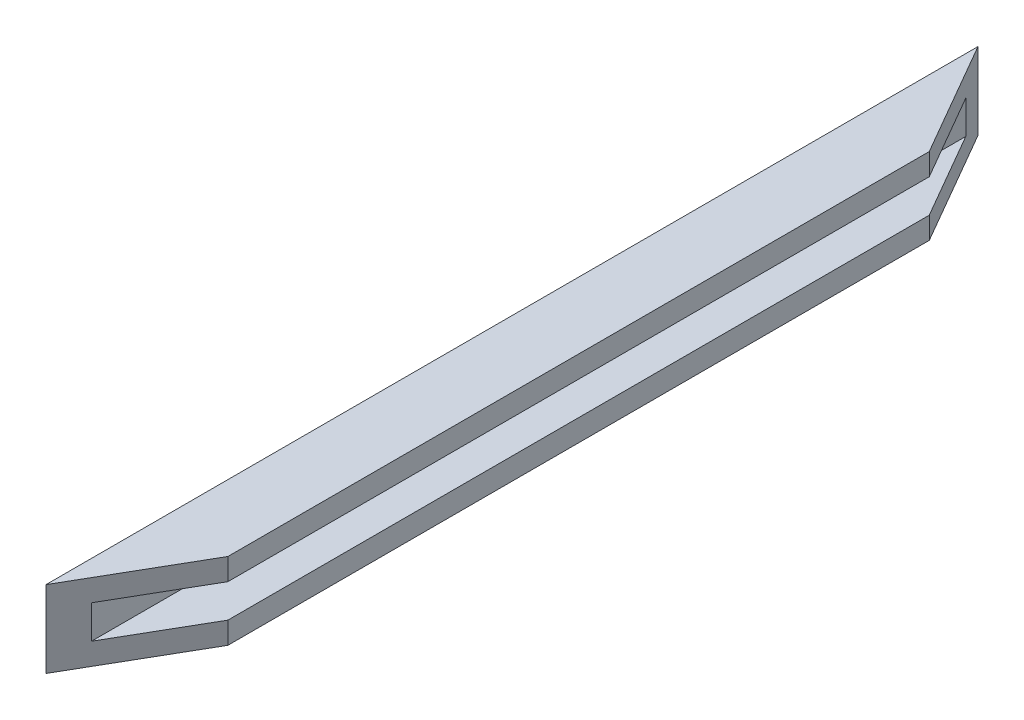
SolidWorks part; units mm, degrees
ref_plane "Front Plane" through (0, 0, 0) normal (0, 0, 1) x (1, 0, 0)
ref_plane "Top Plane" through (0, 0, 0) normal (0, 1, 0) x (1, 0, 0)
ref_plane "Right Plane" through (0, 0, 0) normal (1, 0, 0) x (0, 0, -1)
sketch "Sketch1" plane through (0, 0, 0) normal (1, 0, 0) x (0, 0, -1)
  line L1 (0, 0) -> (88.9, 0)
  line L2 (0, 0) -> (0, 7.3406)
  line L3 (0, 7.3406) -> (88.9, 7.3406)
  line L4 (88.9, 0) -> (88.9, 7.3406)
  dimension "D1" = 7.3406
  dimension "D2" = 88.9
extrude "Boss-Extrude1" add sketch "Sketch1" along normal blind 6.35 contours L3 L4 L1 L2
sketch "Sketch2" plane through (6.35, 0, 0) normal (1, 0, 0) x (0, 0, -1)
  line L0 (44.45, 7.3406) -> (44.45, 0) construction
  line L1 (0, 7.3406) -> (88.9, 7.3406) construction
  line L2 (0, 0) -> (88.9, 0) construction
  line L3 (88.9, 0) -> (88.9, 7.3406) construction
  line L4 (0, 5.2578) -> (88.9, 5.2578)
  line L5 (0, 5.2578) -> (0, 2.0828)
  line L6 (0, 2.0828) -> (88.9, 2.0828)
  line L7 (88.9, 5.2578) -> (88.9, 2.0828)
  line L8 (0, 5.2578) -> (88.9, 2.0828) construction
  line L9 (0, 2.0828) -> (88.9, 5.2578) construction
  point P6 (44.45, 3.6703)
  dimension "D1" = 3.175
extrude "Cut-Extrude2" cut sketch "Sketch2" against normal blind 4.7625 contours L4 L7 L6 L5
sketch "Sketch4" plane through (0, 0, 0) normal (0, -1, 0) x (1, 0, 0)
  line L0 (0, 0) -> (6.35, -10.9985)
  line L1 (6.35, 0) -> (6.35, -88.9) construction
  line L2 (0, 0) -> (0, -88.9) construction
  line L3 (6.35, -10.9985) -> (6.35, 0)
  line L4 (6.35, 0) -> (0, 0)
  line L5 (6.35, -44.45) -> (0, -44.45) construction
  line L6 (6.35, -77.9015) -> (6.35, -88.9)
  line L7 (0, -88.9) -> (6.35, -77.9015)
  line L8 (6.35, -88.9) -> (0, -88.9)
  dimension "D1" = 30
extrude "Cut-Extrude3" cut sketch "Sketch4" against normal blind 7.3406
sketch "Sketch5" plane through (0, 0, 0) normal (-1, 0, 0) x (0, 0, 1)
  line L0 (-44.45, 7.3406) -> (-44.45, 0) construction
  line L1 (0, 7.3406) -> (-88.9, 7.3406) construction
  line L2 (0, 0) -> (-88.9, 0) construction
  line L3 (-76.2, 7.3406) -> (-76.2, 0) construction
  line L4 (-88.9, 0) -> (-88.9, 7.3406) construction
  circle A0 centre (-76.2, 3.6703) radius 1.025
  circle A1 centre (-44.45, 3.6703) radius 1.025
  circle A2 centre (-12.7, 3.6703) radius 1.025
  dimension "D2" = 2.05
  dimension "D1" = 12.7
extrude "Cut-Extrude4" cut sketch "Sketch5" against normal blind 1.5875
equation "\"length\" = 3.5in"
